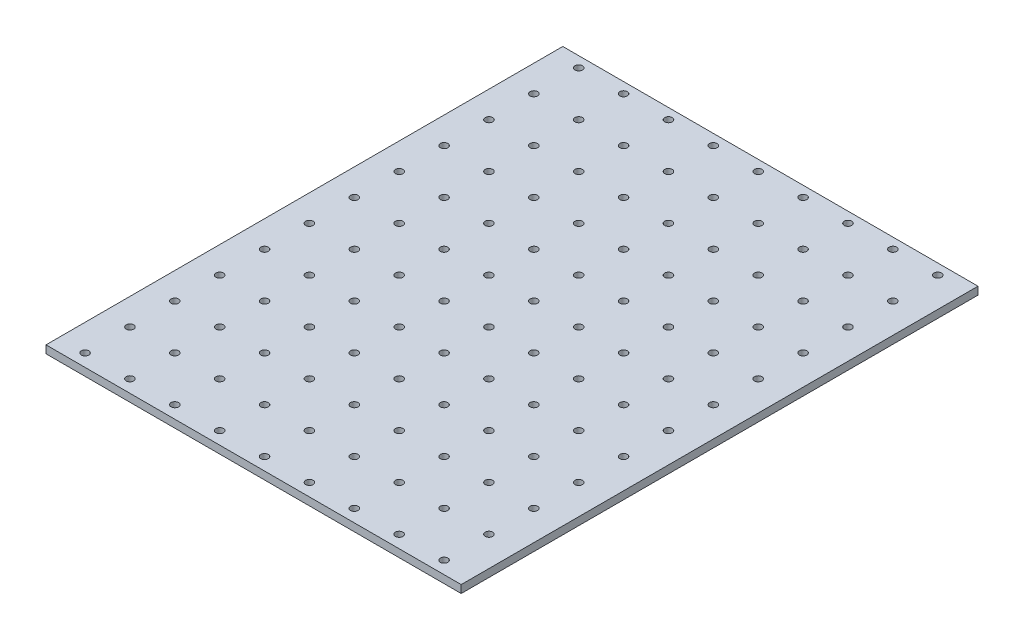
SolidWorks part; units mm, degrees
ref_plane "Front Plane" through (0, 0, 0) normal (0, 0, 1) x (1, 0, 0)
ref_plane "Top Plane" through (0, 0, 0) normal (0, 1, 0) x (1, 0, 0)
ref_plane "Right Plane" through (0, 0, 0) normal (1, 0, 0) x (0, 0, -1)
sketch "Sketch1" plane through (0, 0, 0) normal (0, 1, 0) x (1, 0, 0)
  line L1 (-235, -292.5) -> (235, -292.5)
  line L2 (-235, -292.5) -> (-235, 292.5)
  line L3 (-235, 292.5) -> (235, 292.5)
  line L4 (235, -292.5) -> (235, 292.5)
  line L5 (-235, -292.5) -> (235, 292.5) construction
  line L6 (-235, 292.5) -> (235, -292.5) construction
  point P0 (0, 0)
  dimension "D1" = 470
  dimension "D2" = 585
extrude "Boss-Extrude1" add sketch "Sketch1" along normal blind 8.8
sketch "Sketch2" plane through (0, 8.8, 0) normal (0, 1, 0) x (1, 0, 0)
  line L0 (235, 292.5) -> (-235, 292.5) construction
  line L1 (-235, 292.5) -> (-235, -292.5) construction
  circle A0 centre (-205, 280.5) radius 4.25
  dimension "D3" = 8.5
  dimension "D1" = 12
  dimension "D2" = 30
extrude "Cut-Extrude1" cut sketch "Sketch2" against normal up to surface (8.8 mm away) up to face at (0, 0, 0)
pattern_linear "LPattern1" count 12 spacing 50.8 along (0, 0, 1) count 9 spacing 50.8 along (1, 0, 0) of "Cut-Extrude1"
